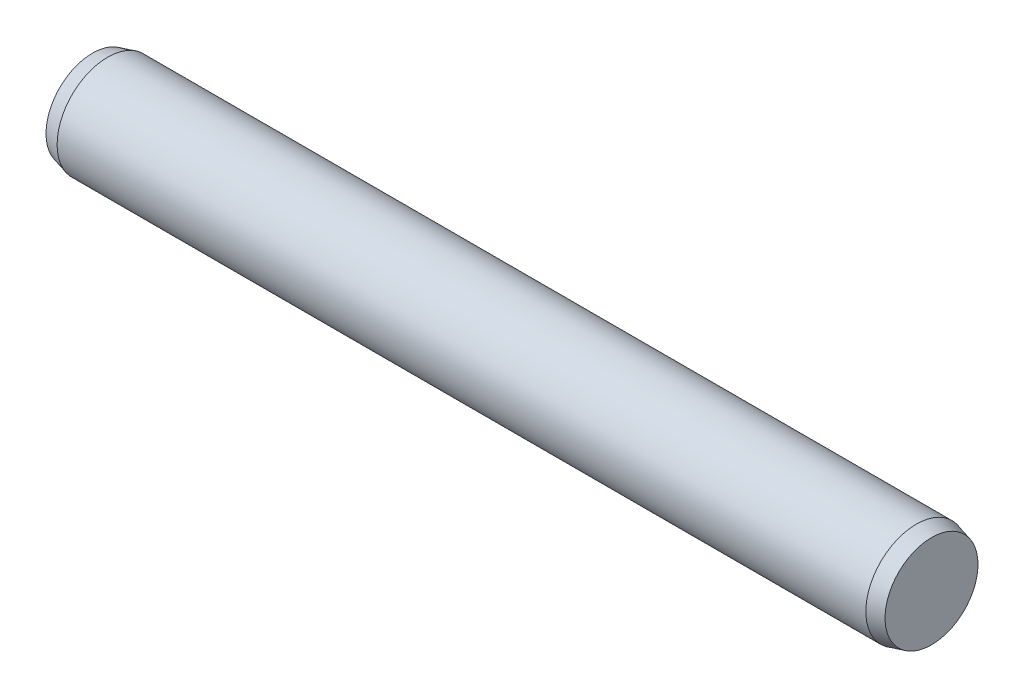
SolidWorks part; units mm, degrees
ref_plane "Front Plane" through (0, 0, 0) normal (0, 0, 1) x (1, 0, 0)
ref_plane "Top Plane" through (0, 0, 0) normal (0, 1, 0) x (1, 0, 0)
ref_plane "Right Plane" through (0, 0, 0) normal (1, 0, 0) x (0, 0, -1)
sketch "Sketch1" plane through (0, 0, 0) normal (0, 0, 1) x (1, 0, 0)
  line L0 (-12, 0) -> (12, 0) construction
  line L1 (12, 1.5) -> (12, -1.5) construction
  line L2 (-12, 1.5) -> (-12, -1.5) construction
  line L3 (12.45, 1.5) -> (12.45, -1.5) construction
  line L4 (-12.45, 1.5) -> (-12.45, -1.5) construction
  line L5 (-12, 0) -> (-12.45, 0) construction
  line L6 (12, 0) -> (12.45, 0) construction
  dimension "D1" = 0.45
  dimension "Dia" = 3
  dimension "Length" = 24
  dimension "C" = 0.45
sketch "Sketch2" plane through (0, 0, 0) normal (1, 0, 0) x (0, 0, -1)
  circle A0 centre (0, 0) radius 1.5
extrude "Extrude1" add sketch "Sketch2" against normal up to vertex (12 mm away) and the other way up to vertex (12 mm away) up to point (-12, 1.5, 0) other way up to point (12, 1.5, 0)
sketch "Sketch3" plane through (12, 0, 0) normal (1, 0, 0) x (0, 0, -1)
  circle A1 centre (0, 0) radius 1.5
  circle A2 centre (0, 0) radius 1.5
  dimension "D1" = 0
extrude "Extrude2" add sketch "Sketch3" along normal up to vertex (0.45 mm away) draft 15 up to point (12.45, 0, 0)
sketch "Sketch4" plane through (-12, 0, 0) normal (-1, 0, 0) x (0, 0, 1)
  circle A1 centre (0, 0) radius 1.5
  circle A2 centre (0, 0) radius 1.5
  dimension "D1" = 0
extrude "Extrude3" add sketch "Sketch4" along normal up to vertex (0.45 mm away) draft 15 up to point (-12.45, 0, 0)
equation "\"D1@Sketch1\" = \"C@Sketch1\""
